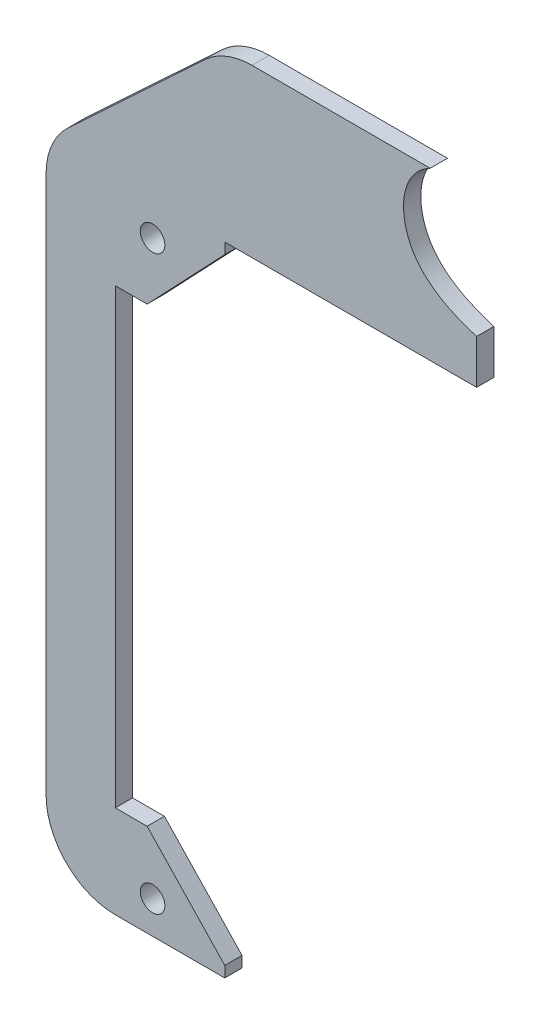
SolidWorks part; units mm, degrees
material "AISI 4340 Steel, annealed"
ref_plane "X-Y Datum" through (0, 0, 0) normal (0, 0, 1) x (1, 0, 0)
ref_plane "X-Z Datum" through (0, 0, 0) normal (0, 1, 0) x (1, 0, 0)
ref_plane "Y-Z Datum" through (0, 0, 0) normal (1, 0, 0) x (0, 0, -1)
sketch3d "3DSketch1"
  line L0 (-464.25, 116.5, 0) -> (-464.25, 118.5, 0)
  line L1 (-464.25, 118.5, 0) -> (-490, 118.5, 0)
  line L2 (-490, 118.5, 0) -> (-490, 1.5, 0)
  line L3 (-490, 1.5, 0) -> (-464.25, 1.5, 0)
  line L12 (-490, 1.5, 0) -> (0, 1.5, 0) construction
  line L13 (-464.25, 3.5, 0) -> (-464.25, 1.5, 0)
  line L14 (0, 118.5, 0) -> (-490, 118.5, 0) construction
  line L15 (-464.25, 3.5, 0) -> (-478.5, 18.5, 0)
  line L16 (-478.5, 18.5, 0) -> (-484.35, 18.5, 0)
  line L17 (-484.35, 18.5, 0) -> (-484.35, 101.5, 0)
  line L18 (-484.35, 101.5, 0) -> (-478.5, 101.5, 0)
  line L19 (-478.5, 101.5, 0) -> (-464.25, 116.5, 0)
  line L20 (-477.5, 7.5, -1) -> (-477.5, 7.5, 0) construction
  line L21 (-477.5, 112.5, -1) -> (-477.5, 112.5, 0) construction
  line L23 (-490, 118.5, 0) -> (-464.25, 118.5, 0)
  line L24 (-490, 118.5, 0) -> (-490, 141.4598, 0)
  line L25 (-490, 141.4598, 0) -> (-464.25, 141.4598, 0)
  line L26 (-464.25, 118.5, 0) -> (-464.25, 141.4598, 0)
  line L27 (-490, 1.5, 0) -> (-497.05, 1.5, 0)
  line L28 (-490, 1.5, 0) -> (-490, 141.4598, 0)
  line L29 (-490, 141.4598, 0) -> (-497.05, 141.4598, 0)
  line L30 (-497.05, 1.5, 0) -> (-497.05, 141.4598, 0)
  circle A0 centre (-477.5, 7.5, 0) radius 2.25
  circle A1 centre (-477.5, 112.5, 0) radius 2.25
  point P24 (-477.5, 7.5, 2.25)
  point P29 (-477.5, 112.5, 2.25)
  dimension "D1" = 4.5
  dimension "D2" = 4.5
  dimension "D3" = 12.7
extrude "Boss-Extrude1" add sketch "3DSketch1" along a picked direction on the side against the normal blind 3.175 contours L0 L1 L2 L3 L13 L15 L16 L17 L18 L19 | L24 L23 L26 L25 | A1 | A0 | L30 L29 L28 L27
sketch "Sketch2" plane through (-464.25, 0, 0) normal (1, 0, 0) x (0, 0, -1)
  line L4 (-3.175, 141.4598) -> (-3.175, 118.5)
  line L5 (-3.175, 118.5) -> (0, 118.5)
  line L6 (0, 118.5) -> (0, 141.4598)
  line L7 (0, 141.4598) -> (-3.175, 141.4598)
  line L8 (-3.175, 141.4598) -> (-3.175, 118.5)
  line L9 (-3.175, 118.5) -> (0, 118.5)
  line L10 (0, 118.5) -> (0, 141.4598)
  line L11 (0, 141.4598) -> (-3.175, 141.4598)
  dimension "D1" = 0
extrude "Boss-Extrude2" add sketch "Sketch2" along normal blind 41.91
sketch "Sketch3" plane through (0, 141.4598, 0) normal (0, 1, 0) x (1, 0, 0)
  line L0 (-497.05, -3.175) -> (-490, -3.175) construction
  line L1 (-490, -3.175) -> (-490, 0) construction
  line L2 (-490, 0) -> (-497.05, 0) construction
  line L3 (-497.05, 0) -> (-497.05, -3.175) construction
  line L4 (-490, -3.175) -> (-422.34, -3.175) construction
  line L5 (-422.34, -3.175) -> (-422.34, 0) construction
  line L6 (-422.34, 0) -> (-490, 0) construction
  line L7 (-490, 0) -> (-490, -3.175) construction
  line L8 (-497.05, -3.175) -> (-490, -3.175)
  line L9 (-490, -3.175) -> (-490, 0)
  line L10 (-490, 0) -> (-497.05, 0)
  line L11 (-497.05, 0) -> (-497.05, -3.175)
  line L12 (-490, -3.175) -> (-422.34, -3.175)
  line L13 (-422.34, -3.175) -> (-422.34, 0)
  line L14 (-422.34, 0) -> (-490, 0)
  line L15 (-490, 0) -> (-490, -3.175)
  line M1 (-490, -3.175) -> (-422.34, -3.175)
  line M2 (-422.34, -3.175) -> (-422.34, 0)
  line M3 (-422.34, 0) -> (-490, 0)
  line M4 (-490, 0) -> (-490, -3.175)
extrude "Boss-Extrude3" add sketch "Sketch3" along normal blind 7.62 contours M4 M1 M2 M3 | L10 L11 L8 M4
sketch "Sketch4" plane through (-422.34, 0, 0) normal (1, 0, 0) x (0, 0, -1)
  line L4 (-3.175, 149.0798) -> (-3.175, 118.5)
  line L5 (-3.175, 118.5) -> (0, 118.5)
  line L6 (0, 118.5) -> (0, 149.0798)
  line L7 (0, 149.0798) -> (-3.175, 149.0798)
  line L8 (-3.175, 149.0798) -> (-3.175, 118.5)
  line L9 (-3.175, 118.5) -> (0, 118.5)
  line L10 (0, 118.5) -> (0, 149.0798)
  line L11 (0, 149.0798) -> (-3.175, 149.0798)
  dimension "D1" = 0
extrude "Boss-Extrude4" add sketch "Sketch4" along normal blind 4.318
sketch "Sketch5" plane through (0, 0, 3.175) normal (0, 0, 1) x (1, 0, 0)
  line L0 (-418.022, 149.0798) -> (-418.022, 118.5) construction
  line L1 (-497.05, 149.0798) -> (-418.022, 149.0798) construction
  line L2 (-426.5391, 149.0798) -> (-418.022, 149.0798)
  line L3 (-418.022, 149.0798) -> (-418.022, 126.6063)
  line L4 (-497.05, 118.5) -> (-464.25, 149.0798)
  line L5 (-497.05, 1.5) -> (-497.05, 149.0798) construction
  line L6 (-464.25, 149.0798) -> (-497.05, 149.0798)
  line L7 (-497.05, 149.0798) -> (-497.05, 118.5)
  spline S0 degree 3 poles (-418.022, 126.6063) (-422.2068, 127.8413) (-432.7077, 132.5927) (-432.3638, 146.0229) (-426.5391, 149.0798) knots 0 0 0 0 0.445071 1 1 1 1
extrude "Cut-Extrude1" cut sketch "Sketch5" against normal blind 5.08
fillet "Fillet1" radius 12.7 3 edges at (-464.25, 149.0798, 1.5875) (-497.05, 118.5, 1.5875)
